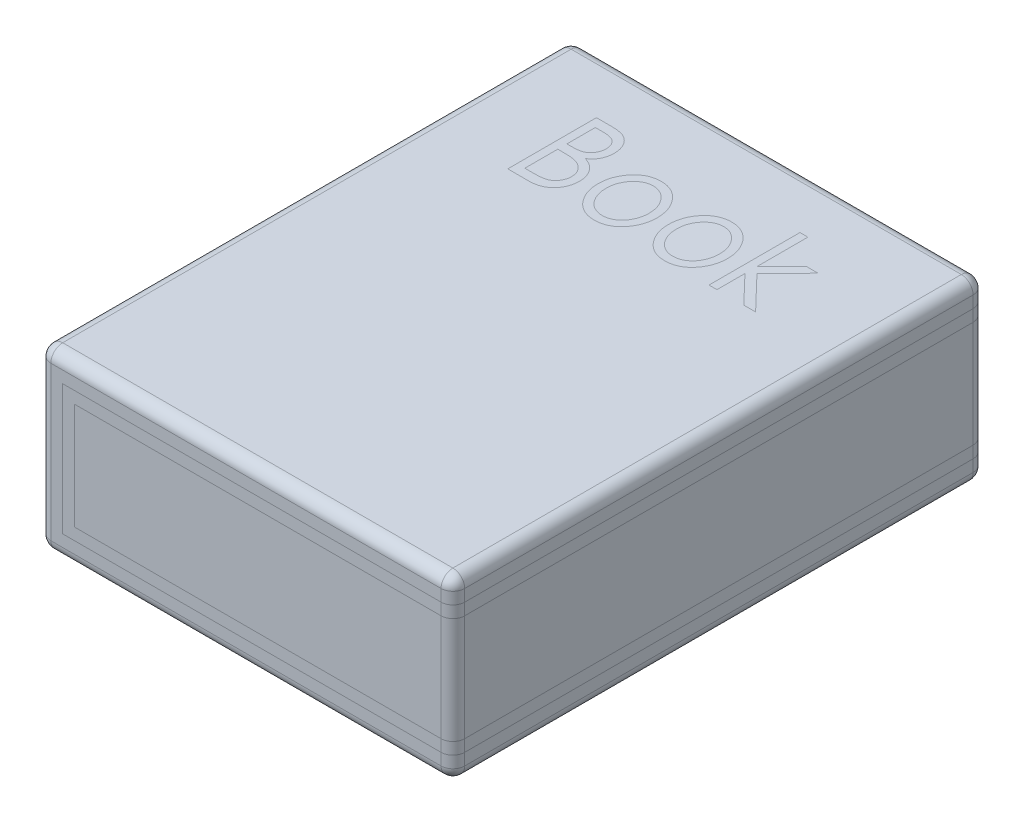
SolidWorks part; units mm, degrees
material "ABS"
ref_plane "Front Plane" through (0, 0, 0) normal (0, 0, 1) x (1, 0, 0)
ref_plane "Top Plane" through (0, 0, 0) normal (0, 1, 0) x (1, 0, 0)
ref_plane "Right Plane" through (0, 0, 0) normal (1, 0, 0) x (0, 0, -1)
sketch "Sketch1" plane through (0, 0, 0) normal (0, 1, 0) x (1, 0, 0)
  line L1 (-3.5, -4.5) -> (3.5, -4.5)
  line L2 (-3.5, -4.5) -> (-3.5, 4.5)
  line L3 (-3.5, 4.5) -> (3.5, 4.5)
  line L4 (3.5, -4.5) -> (3.5, 4.5)
  line L5 (-3.5, -4.5) -> (3.5, 4.5) construction
  line L6 (-3.5, 4.5) -> (3.5, -4.5) construction
  point P0 (0, 0)
  dimension "D1" = 7
  dimension "D2" = 9
extrude "Book" add sketch "Sketch1" along normal blind 3
sketch "Sketch2" plane through (0, 0, -4.5) normal (0, 0, -1) x (-1, 0, 0)
  line L0 (-3.5, 0) -> (3.5, 0) construction
  line L1 (3.1, 0.4) -> (-8.9, 0.4)
  line L2 (3.1, 0.4) -> (3.1, 2.6)
  line L3 (3.1, 2.6) -> (-8.9, 2.6)
  line L4 (-8.9, 0.4) -> (-8.9, 2.6)
  line L5 (3.5, 3) -> (3.5, 0) construction
  line L6 (-3.5, 3) -> (3.5, 3) construction
  line L8 (2.9, 2.4) -> (-8.8, 2.4)
  line L9 (2.9, 2.4) -> (2.9, 0.6)
  line L10 (2.9, 0.6) -> (-8.8, 0.6)
  line L11 (-8.8, 2.4) -> (-8.8, 0.6)
  dimension "D1" = 0.4
  dimension "D2" = 0.4
  dimension "D3" = 0.4
  dimension "D4" = 12
  dimension "D5" = 0.2
  dimension "D6" = 0.2
  dimension "D7" = 0.2
  dimension "D8" = 0.1
split line "Pages"
fillet "Smoothing edges" radius 0.2 20 edges at (3.5, 2.8, 4.5) (3.5, 0.2, 4.5) (3.5, 2.5, 4.5) (3.5, 0.5, 4.5) (3.5, 1.5, 4.5) (3.5, 2.8, -4.5) (3.5, 0.2, -4.5) (3.5, 0.5, -4.5) (3.5, 2.5, -4.5) (3.5, 1.5, -4.5) (0, 0, -4.5) (-3.5, 0, 0) (0, 0, 4.5) (3.5, 0, 0) (0, 3, 4.5) (-3.5, 3, 0) (0, 3, -4.5) (3.5, 3, 0) (-3.5, 1.5, 4.5) (-3.5, 1.5, -4.5)
sketch "Sketch3" plane through (0, 3, 0) normal (0, 1, 0) x (1, 0, 0)
  text T0 "Book" font "Century Gothic" height 1.5
split line "Word \"book\""
